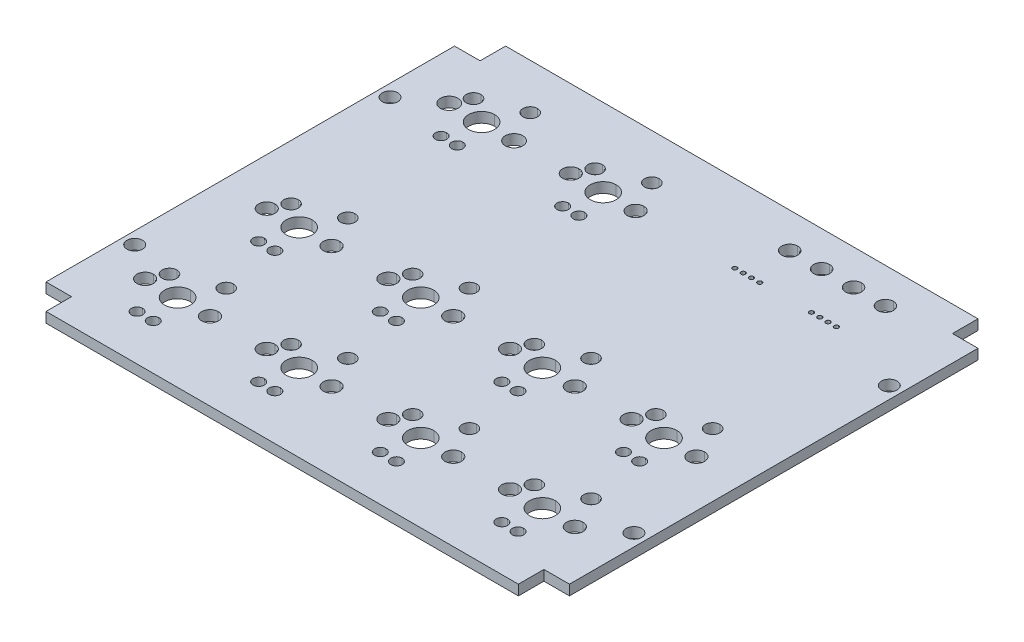
SolidWorks part; units mm, degrees
material "Copper"
ref_plane "Front" through (0, 0, 0) normal (0, 0, 1) x (1, 0, 0)
ref_plane "Top" through (0, 0, 0) normal (0, 1, 0) x (1, 0, 0)
ref_plane "Right" through (0, 0, 0) normal (1, 0, 0) x (0, 0, -1)
sketch "Sketch1" plane through (0, 0, 0) normal (0, 1, 0) x (1, 0, 0)
  line L0 (-41, 32) -> (-37, 32)
  line L1 (-37, 36) -> (37, 36)
  line L2 (-41, 32) -> (-41, -32)
  line L3 (-37, -36) -> (37, -36)
  line L4 (41, 32) -> (41, -32)
  line L5 (37, 36) -> (37, 32)
  line L6 (37, 32) -> (41, 32)
  line L7 (-37, 32) -> (-37, 36)
  line L8 (37, -36) -> (37, -32)
  line L9 (37, -32) -> (41, -32)
  line L10 (-37, -36) -> (-37, -32)
  line L11 (-37, -32) -> (-41, -32)
  line L12 (0, 36) -> (0, -36) construction
  dimension "D1" = 72
  dimension "D2" = 82
  dimension "D3" = 4
extrude "Boss-Extrude1" add sketch "Sketch1" along normal blind 1.6
sketch "Sketch2" plane through (0, 1.6, 0) normal (0, 1, 0) x (1, 0, 0)
  line L0 (-37, -36) -> (37, -36) construction
  line L1 (-41, 32) -> (-41, -32) construction
  line B0 (-41, -32) -> (-37, -32) construction
  line B1 (-37, -32) -> (-37, -36) construction
  line B2 (-37, -36) -> (36.9998, -36) construction
  line B3 (36.9998, -36) -> (36.9998, -32) construction
  line B4 (36.9998, -32) -> (40.9998, -32) construction
  line B5 (40.9998, -32) -> (40.9998, 31.9998) construction
  line B6 (40.9998, 31.9998) -> (36.9998, 31.9998) construction
  line B7 (36.9998, 31.9998) -> (36.9998, 35.9998) construction
  line B8 (36.9998, 35.9998) -> (-37, 35.9998) construction
  line B9 (-37, 35.9998) -> (-37, 31.9998) construction
  line B10 (-37, 31.9998) -> (-41, 31.9998) construction
  line B11 (-41, 31.9998) -> (-41, -32) construction
  spline B12 degree 3 poles (-28.5761, 21.7818) (-29.6983, 21.7818) (-30.6081, 22.6916) (-30.6081, 24.936) (-29.6983, 25.8458) (-28.5761, 25.8458) knots 2 2 2 2 3 3 4 4 4 4
  spline B13 degree 3 poles (-28.5761, 25.8458) (-27.4539, 25.8458) (-26.5441, 24.936) (-26.5441, 22.6916) (-27.4539, 21.7818) (-28.5761, 21.7818) knots 0 0 0 0 1 1 2 2 2 2
  spline B14 degree 3 poles (-9.5261, 21.7818) (-10.6484, 21.7818) (-11.5581, 22.6916) (-11.5581, 24.936) (-10.6484, 25.8458) (-9.5261, 25.8458) knots 2 2 2 2 3 3 4 4 4 4
  spline B15 degree 3 poles (-9.5261, 25.8458) (-8.4039, 25.8458) (-7.4942, 24.936) (-7.4942, 22.6916) (-8.4039, 21.7818) (-9.5261, 21.7818) knots 0 0 0 0 1 1 2 2 2 2
  spline B16 degree 3 poles (-28.5761, -6.7942) (-29.6983, -6.7942) (-30.6081, -5.8844) (-30.6081, -3.6399) (-29.6983, -2.7302) (-28.5761, -2.7302) knots 2 2 2 2 3 3 4 4 4 4
  spline B17 degree 3 poles (-28.5761, -2.7302) (-27.4539, -2.7302) (-26.5441, -3.6399) (-26.5441, -5.8844) (-27.4539, -6.7942) (-28.5761, -6.7942) knots 0 0 0 0 1 1 2 2 2 2
  spline B18 degree 3 poles (-9.5261, -6.7942) (-10.6484, -6.7942) (-11.5581, -5.8844) (-11.5581, -3.6399) (-10.6484, -2.7302) (-9.5261, -2.7302) knots 2 2 2 2 3 3 4 4 4 4
  spline B19 degree 3 poles (-9.5261, -2.7302) (-8.4039, -2.7302) (-7.4942, -3.6399) (-7.4942, -5.8844) (-8.4039, -6.7942) (-9.5261, -6.7942) knots 0 0 0 0 1 1 2 2 2 2
  spline B20 degree 3 poles (9.5238, -6.7942) (8.4015, -6.7942) (7.4918, -5.8844) (7.4918, -3.6399) (8.4015, -2.7302) (9.5238, -2.7302) knots 2 2 2 2 3 3 4 4 4 4
  spline B21 degree 3 poles (9.5238, -2.7302) (10.6461, -2.7302) (11.5558, -3.6399) (11.5558, -5.8844) (10.6461, -6.7942) (9.5238, -6.7942) knots 0 0 0 0 1 1 2 2 2 2
  spline B22 degree 3 poles (28.5738, -6.7942) (27.4515, -6.7942) (26.5418, -5.8844) (26.5418, -3.6399) (27.4515, -2.7302) (28.5738, -2.7302) knots 2 2 2 2 3 3 4 4 4 4
  spline B23 degree 3 poles (28.5738, -2.7302) (29.6961, -2.7302) (30.6058, -3.6399) (30.6058, -5.8844) (29.6961, -6.7942) (28.5738, -6.7942) knots 0 0 0 0 1 1 2 2 2 2
  spline B24 degree 3 poles (-28.5761, -25.8441) (-29.6983, -25.8441) (-30.6081, -24.9343) (-30.6081, -22.6899) (-29.6983, -21.7801) (-28.5761, -21.7801) knots 2 2 2 2 3 3 4 4 4 4
  spline B25 degree 3 poles (-28.5761, -21.7801) (-27.4539, -21.7801) (-26.5441, -22.6899) (-26.5441, -24.9343) (-27.4539, -25.8441) (-28.5761, -25.8441) knots 0 0 0 0 1 1 2 2 2 2
  spline B26 degree 3 poles (-9.5261, -25.8441) (-10.6484, -25.8441) (-11.5581, -24.9343) (-11.5581, -22.6899) (-10.6484, -21.7801) (-9.5261, -21.7801) knots 2 2 2 2 3 3 4 4 4 4
  spline B27 degree 3 poles (-9.5261, -21.7801) (-8.4039, -21.7801) (-7.4942, -22.6899) (-7.4942, -24.9343) (-8.4039, -25.8441) (-9.5261, -25.8441) knots 0 0 0 0 1 1 2 2 2 2
  spline B28 degree 3 poles (9.5238, -25.8441) (8.4015, -25.8441) (7.4918, -24.9343) (7.4918, -22.6899) (8.4015, -21.7801) (9.5238, -21.7801) knots 2 2 2 2 3 3 4 4 4 4
  spline B29 degree 3 poles (9.5238, -21.7801) (10.6461, -21.7801) (11.5558, -22.6899) (11.5558, -24.9343) (10.6461, -25.8441) (9.5238, -25.8441) knots 0 0 0 0 1 1 2 2 2 2
  spline B30 degree 3 poles (28.5738, -25.8441) (27.4515, -25.8441) (26.5418, -24.9343) (26.5418, -22.6899) (27.4515, -21.7801) (28.5738, -21.7801) knots 2 2 2 2 3 3 4 4 4 4
  spline B31 degree 3 poles (28.5738, -21.7801) (29.6961, -21.7801) (30.6058, -22.6899) (30.6058, -24.9343) (29.6961, -25.8441) (28.5738, -25.8441) knots 0 0 0 0 1 1 2 2 2 2
  spline B32 degree 3 poles (12.9998, 29.2499) (12.3095, 29.2499) (11.7498, 29.8095) (11.7498, 31.1902) (12.3095, 31.7498) (12.9998, 31.7498) knots 2 2 2 2 3 3 4 4 4 4
  spline B33 degree 3 poles (12.9998, 31.7498) (13.6901, 31.7498) (14.2498, 31.1902) (14.2498, 29.8095) (13.6901, 29.2499) (12.9998, 29.2499) knots 0 0 0 0 1 1 2 2 2 2
  spline B34 degree 3 poles (23, 29.2499) (22.3097, 29.2499) (21.75, 29.8095) (21.75, 31.1902) (22.3097, 31.7498) (23, 31.7498) knots 2 2 2 2 3 3 4 4 4 4
  spline B35 degree 3 poles (23, 31.7498) (23.6904, 31.7498) (24.2501, 31.1902) (24.2501, 29.8095) (23.6904, 29.2499) (23, 29.2499) knots 0 0 0 0 1 1 2 2 2 2
  spline B36 degree 3 poles (27.9999, 29.2499) (27.3096, 29.2499) (26.7499, 29.8095) (26.7499, 31.1902) (27.3096, 31.7498) (27.9999, 31.7498) knots 2 2 2 2 3 3 4 4 4 4
  spline B37 degree 3 poles (27.9999, 31.7498) (28.6902, 31.7498) (29.2499, 31.1902) (29.2499, 29.8095) (28.6902, 29.2499) (27.9999, 29.2499) knots 0 0 0 0 1 1 2 2 2 2
  spline B38 degree 3 poles (17.9998, 29.2499) (17.3095, 29.2499) (16.7498, 29.8095) (16.7498, 31.1902) (17.3095, 31.7498) (17.9998, 31.7498) knots 2 2 2 2 3 3 4 4 4 4
  spline B39 degree 3 poles (17.9998, 31.7498) (18.6901, 31.7498) (19.2498, 31.1902) (19.2498, 29.8095) (18.6901, 29.2499) (17.9998, 29.2499) knots 0 0 0 0 1 1 2 2 2 2
  spline B40 degree 3 poles (-32.3861, 25.2108) (-33.0174, 25.2108) (-33.5291, 25.7225) (-33.5291, 26.9851) (-33.0174, 27.4968) (-32.3861, 27.4968) knots 2 2 2 2 3 3 4 4 4 4
  spline B41 degree 3 poles (-32.3861, 27.4968) (-31.7548, 27.4968) (-31.2431, 26.9851) (-31.2431, 25.7225) (-31.7548, 25.2108) (-32.3861, 25.2108) knots 0 0 0 0 1 1 2 2 2 2
  spline B42 degree 3 poles (-26.0361, 27.7508) (-26.6674, 27.7508) (-27.1791, 28.2625) (-27.1791, 29.5251) (-26.6674, 30.0368) (-26.0361, 30.0368) knots 2 2 2 2 3 3 4 4 4 4
  spline B43 degree 3 poles (-26.0361, 30.0368) (-25.4048, 30.0368) (-24.8931, 29.5251) (-24.8931, 28.2625) (-25.4048, 27.7508) (-26.0361, 27.7508) knots 0 0 0 0 1 1 2 2 2 2
  spline B44 degree 3 poles (-33.6561, 22.5281) (-34.3662, 22.5281) (-34.9418, 23.1037) (-34.9418, 24.5239) (-34.3662, 25.0996) (-33.6561, 25.0996) knots 2 2 2 2 3 3 4 4 4 4
  spline B45 degree 3 poles (-33.6561, 25.0996) (-32.946, 25.0996) (-32.3703, 24.5239) (-32.3703, 23.1037) (-32.946, 22.5281) (-33.6561, 22.5281) knots 0 0 0 0 1 1 2 2 2 2
  spline B46 degree 3 poles (-23.4961, 22.5281) (-24.2062, 22.5281) (-24.7819, 23.1037) (-24.7819, 24.5239) (-24.2062, 25.0996) (-23.4961, 25.0996) knots 2 2 2 2 3 3 4 4 4 4
  spline B47 degree 3 poles (-23.4961, 25.0996) (-22.786, 25.0996) (-22.2104, 24.5239) (-22.2104, 23.1037) (-22.786, 22.5281) (-23.4961, 22.5281) knots 0 0 0 0 1 1 2 2 2 2
  spline B48 degree 3 poles (-29.8461, 17.8448) (-30.3371, 17.8448) (-30.7351, 18.2428) (-30.7351, 19.2248) (-30.3371, 19.6228) (-29.8461, 19.6228) knots 2 2 2 2 3 3 4 4 4 4
  spline B49 degree 3 poles (-29.8461, 19.6228) (-29.3551, 19.6228) (-28.9571, 19.2248) (-28.9571, 18.2428) (-29.3551, 17.8448) (-29.8461, 17.8448) knots 0 0 0 0 1 1 2 2 2 2
  spline B50 degree 3 poles (-27.3061, 17.8448) (-27.7971, 17.8448) (-28.1951, 18.2428) (-28.1951, 19.2248) (-27.7971, 19.6228) (-27.3061, 19.6228) knots 2 2 2 2 3 3 4 4 4 4
  spline B51 degree 3 poles (-27.3061, 19.6228) (-26.8151, 19.6228) (-26.4171, 19.2248) (-26.4171, 18.2428) (-26.8151, 17.8448) (-27.3061, 17.8448) knots 0 0 0 0 1 1 2 2 2 2
  spline B52 degree 3 poles (-13.3361, 25.2108) (-13.9674, 25.2108) (-14.4791, 25.7225) (-14.4791, 26.9851) (-13.9674, 27.4968) (-13.3361, 27.4968) knots 2 2 2 2 3 3 4 4 4 4
  spline B53 degree 3 poles (-13.3361, 27.4968) (-12.7049, 27.4968) (-12.1931, 26.9851) (-12.1931, 25.7225) (-12.7049, 25.2108) (-13.3361, 25.2108) knots 0 0 0 0 1 1 2 2 2 2
  spline B54 degree 3 poles (-6.9862, 27.7508) (-7.6174, 27.7508) (-8.1292, 28.2625) (-8.1292, 29.5251) (-7.6174, 30.0368) (-6.9862, 30.0368) knots 2 2 2 2 3 3 4 4 4 4
  spline B55 degree 3 poles (-6.9862, 30.0368) (-6.3549, 30.0368) (-5.8432, 29.5251) (-5.8432, 28.2625) (-6.3549, 27.7508) (-6.9862, 27.7508) knots 0 0 0 0 1 1 2 2 2 2
  spline B56 degree 3 poles (-14.6061, 22.5281) (-15.3163, 22.5281) (-15.8919, 23.1037) (-15.8919, 24.5239) (-15.3163, 25.0996) (-14.6061, 25.0996) knots 2 2 2 2 3 3 4 4 4 4
  spline B57 degree 3 poles (-14.6061, 25.0996) (-13.896, 25.0996) (-13.3204, 24.5239) (-13.3204, 23.1037) (-13.896, 22.5281) (-14.6061, 22.5281) knots 0 0 0 0 1 1 2 2 2 2
  spline B58 degree 3 poles (-4.4462, 22.5281) (-5.1563, 22.5281) (-5.7319, 23.1037) (-5.7319, 24.5239) (-5.1563, 25.0996) (-4.4462, 25.0996) knots 2 2 2 2 3 3 4 4 4 4
  spline B59 degree 3 poles (-4.4462, 25.0996) (-3.736, 25.0996) (-3.1604, 24.5239) (-3.1604, 23.1037) (-3.736, 22.5281) (-4.4462, 22.5281) knots 0 0 0 0 1 1 2 2 2 2
  spline B60 degree 3 poles (-10.7961, 17.8448) (-11.2872, 17.8448) (-11.6851, 18.2428) (-11.6851, 19.2248) (-11.2872, 19.6228) (-10.7961, 19.6228) knots 2 2 2 2 3 3 4 4 4 4
  spline B61 degree 3 poles (-10.7961, 19.6228) (-10.3051, 19.6228) (-9.9071, 19.2248) (-9.9071, 18.2428) (-10.3051, 17.8448) (-10.7961, 17.8448) knots 0 0 0 0 1 1 2 2 2 2
  spline B62 degree 3 poles (-8.2562, 17.8448) (-8.7472, 17.8448) (-9.1451, 18.2428) (-9.1451, 19.2248) (-8.7472, 19.6228) (-8.2562, 19.6228) knots 2 2 2 2 3 3 4 4 4 4
  spline B63 degree 3 poles (-8.2562, 19.6228) (-7.7651, 19.6228) (-7.3672, 19.2248) (-7.3672, 18.2428) (-7.7651, 17.8448) (-8.2562, 17.8448) knots 0 0 0 0 1 1 2 2 2 2
  spline B64 degree 3 poles (-32.3861, -3.3652) (-33.0174, -3.3652) (-33.5291, -2.8534) (-33.5291, -1.5909) (-33.0174, -1.0792) (-32.3861, -1.0792) knots 2 2 2 2 3 3 4 4 4 4
  spline B65 degree 3 poles (-32.3861, -1.0792) (-31.7548, -1.0792) (-31.2431, -1.5909) (-31.2431, -2.8534) (-31.7548, -3.3652) (-32.3861, -3.3652) knots 0 0 0 0 1 1 2 2 2 2
  spline B66 degree 3 poles (-26.0361, -0.8252) (-26.6674, -0.8252) (-27.1791, -0.3135) (-27.1791, 0.9491) (-26.6674, 1.4608) (-26.0361, 1.4608) knots 2 2 2 2 3 3 4 4 4 4
  spline B67 degree 3 poles (-26.0361, 1.4608) (-25.4048, 1.4608) (-24.8931, 0.9491) (-24.8931, -0.3135) (-25.4048, -0.8252) (-26.0361, -0.8252) knots 0 0 0 0 1 1 2 2 2 2
  spline B68 degree 3 poles (-33.6561, -6.0479) (-34.3662, -6.0479) (-34.9418, -5.4723) (-34.9418, -4.0521) (-34.3662, -3.4764) (-33.6561, -3.4764) knots 2 2 2 2 3 3 4 4 4 4
  spline B69 degree 3 poles (-33.6561, -3.4764) (-32.946, -3.4764) (-32.3703, -4.0521) (-32.3703, -5.4723) (-32.946, -6.0479) (-33.6561, -6.0479) knots 0 0 0 0 1 1 2 2 2 2
  spline B70 degree 3 poles (-23.4961, -6.0479) (-24.2062, -6.0479) (-24.7819, -5.4723) (-24.7819, -4.0521) (-24.2062, -3.4764) (-23.4961, -3.4764) knots 2 2 2 2 3 3 4 4 4 4
  spline B71 degree 3 poles (-23.4961, -3.4764) (-22.786, -3.4764) (-22.2104, -4.0521) (-22.2104, -5.4723) (-22.786, -6.0479) (-23.4961, -6.0479) knots 0 0 0 0 1 1 2 2 2 2
  spline B72 degree 3 poles (-29.8461, -10.7312) (-30.3371, -10.7312) (-30.7351, -10.3332) (-30.7351, -9.3511) (-30.3371, -8.9532) (-29.8461, -8.9532) knots 2 2 2 2 3 3 4 4 4 4
  spline B73 degree 3 poles (-29.8461, -8.9532) (-29.3551, -8.9532) (-28.9571, -9.3511) (-28.9571, -10.3332) (-29.3551, -10.7312) (-29.8461, -10.7312) knots 0 0 0 0 1 1 2 2 2 2
  spline B74 degree 3 poles (-27.3061, -10.7312) (-27.7971, -10.7312) (-28.1951, -10.3332) (-28.1951, -9.3511) (-27.7971, -8.9532) (-27.3061, -8.9532) knots 2 2 2 2 3 3 4 4 4 4
  spline B75 degree 3 poles (-27.3061, -8.9532) (-26.8151, -8.9532) (-26.4171, -9.3511) (-26.4171, -10.3332) (-26.8151, -10.7312) (-27.3061, -10.7312) knots 0 0 0 0 1 1 2 2 2 2
  spline B76 degree 3 poles (-13.3361, -3.3652) (-13.9674, -3.3652) (-14.4791, -2.8534) (-14.4791, -1.5909) (-13.9674, -1.0792) (-13.3361, -1.0792) knots 2 2 2 2 3 3 4 4 4 4
  spline B77 degree 3 poles (-13.3361, -1.0792) (-12.7049, -1.0792) (-12.1931, -1.5909) (-12.1931, -2.8534) (-12.7049, -3.3652) (-13.3361, -3.3652) knots 0 0 0 0 1 1 2 2 2 2
  spline B78 degree 3 poles (-6.9862, -0.8252) (-7.6174, -0.8252) (-8.1292, -0.3135) (-8.1292, 0.9491) (-7.6174, 1.4608) (-6.9862, 1.4608) knots 2 2 2 2 3 3 4 4 4 4
  spline B79 degree 3 poles (-6.9862, 1.4608) (-6.3549, 1.4608) (-5.8432, 0.9491) (-5.8432, -0.3135) (-6.3549, -0.8252) (-6.9862, -0.8252) knots 0 0 0 0 1 1 2 2 2 2
  spline B80 degree 3 poles (-14.6061, -6.0479) (-15.3163, -6.0479) (-15.8919, -5.4723) (-15.8919, -4.0521) (-15.3163, -3.4764) (-14.6061, -3.4764) knots 2 2 2 2 3 3 4 4 4 4
  spline B81 degree 3 poles (-14.6061, -3.4764) (-13.896, -3.4764) (-13.3204, -4.0521) (-13.3204, -5.4723) (-13.896, -6.0479) (-14.6061, -6.0479) knots 0 0 0 0 1 1 2 2 2 2
  spline B82 degree 3 poles (-4.4462, -6.0479) (-5.1563, -6.0479) (-5.7319, -5.4723) (-5.7319, -4.0521) (-5.1563, -3.4764) (-4.4462, -3.4764) knots 2 2 2 2 3 3 4 4 4 4
  spline B83 degree 3 poles (-4.4462, -3.4764) (-3.736, -3.4764) (-3.1604, -4.0521) (-3.1604, -5.4723) (-3.736, -6.0479) (-4.4462, -6.0479) knots 0 0 0 0 1 1 2 2 2 2
  spline B84 degree 3 poles (-10.7961, -10.7312) (-11.2872, -10.7312) (-11.6851, -10.3332) (-11.6851, -9.3511) (-11.2872, -8.9532) (-10.7961, -8.9532) knots 2 2 2 2 3 3 4 4 4 4
  spline B85 degree 3 poles (-10.7961, -8.9532) (-10.3051, -8.9532) (-9.9071, -9.3511) (-9.9071, -10.3332) (-10.3051, -10.7312) (-10.7961, -10.7312) knots 0 0 0 0 1 1 2 2 2 2
  spline B86 degree 3 poles (-8.2562, -10.7312) (-8.7472, -10.7312) (-9.1451, -10.3332) (-9.1451, -9.3511) (-8.7472, -8.9532) (-8.2562, -8.9532) knots 2 2 2 2 3 3 4 4 4 4
  spline B87 degree 3 poles (-8.2562, -8.9532) (-7.7651, -8.9532) (-7.3672, -9.3511) (-7.3672, -10.3332) (-7.7651, -10.7312) (-8.2562, -10.7312) knots 0 0 0 0 1 1 2 2 2 2
  spline B88 degree 3 poles (5.7138, -3.3652) (5.0825, -3.3652) (4.5708, -2.8534) (4.5708, -1.5909) (5.0825, -1.0792) (5.7138, -1.0792) knots 2 2 2 2 3 3 4 4 4 4
  spline B89 degree 3 poles (5.7138, -1.0792) (6.3451, -1.0792) (6.8568, -1.5909) (6.8568, -2.8534) (6.3451, -3.3652) (5.7138, -3.3652) knots 0 0 0 0 1 1 2 2 2 2
  spline B90 degree 3 poles (12.0638, -0.8252) (11.4325, -0.8252) (10.9208, -0.3135) (10.9208, 0.9491) (11.4325, 1.4608) (12.0638, 1.4608) knots 2 2 2 2 3 3 4 4 4 4
  spline B91 degree 3 poles (12.0638, 1.4608) (12.6951, 1.4608) (13.2068, 0.9491) (13.2068, -0.3135) (12.6951, -0.8252) (12.0638, -0.8252) knots 0 0 0 0 1 1 2 2 2 2
  spline B92 degree 3 poles (4.4438, -6.0479) (3.7337, -6.0479) (3.1581, -5.4723) (3.1581, -4.0521) (3.7337, -3.4764) (4.4438, -3.4764) knots 2 2 2 2 3 3 4 4 4 4
  spline B93 degree 3 poles (4.4438, -3.4764) (5.154, -3.4764) (5.7296, -4.0521) (5.7296, -5.4723) (5.154, -6.0479) (4.4438, -6.0479) knots 0 0 0 0 1 1 2 2 2 2
  spline B94 degree 3 poles (14.6038, -6.0479) (13.8936, -6.0479) (13.318, -5.4723) (13.318, -4.0521) (13.8936, -3.4764) (14.6038, -3.4764) knots 2 2 2 2 3 3 4 4 4 4
  spline B95 degree 3 poles (14.6038, -3.4764) (15.314, -3.4764) (15.8895, -4.0521) (15.8895, -5.4723) (15.314, -6.0479) (14.6038, -6.0479) knots 0 0 0 0 1 1 2 2 2 2
  spline B96 degree 3 poles (8.2538, -10.7312) (7.7628, -10.7312) (7.3648, -10.3332) (7.3648, -9.3511) (7.7628, -8.9532) (8.2538, -8.9532) knots 2 2 2 2 3 3 4 4 4 4
  spline B97 degree 3 poles (8.2538, -8.9532) (8.7448, -8.9532) (9.1428, -9.3511) (9.1428, -10.3332) (8.7448, -10.7312) (8.2538, -10.7312) knots 0 0 0 0 1 1 2 2 2 2
  spline B98 degree 3 poles (10.7938, -10.7312) (10.3028, -10.7312) (9.9048, -10.3332) (9.9048, -9.3511) (10.3028, -8.9532) (10.7938, -8.9532) knots 2 2 2 2 3 3 4 4 4 4
  spline B99 degree 3 poles (10.7938, -8.9532) (11.2848, -8.9532) (11.6828, -9.3511) (11.6828, -10.3332) (11.2848, -10.7312) (10.7938, -10.7312) knots 0 0 0 0 1 1 2 2 2 2
  spline B100 degree 3 poles (24.7638, -3.3652) (24.1325, -3.3652) (23.6208, -2.8534) (23.6208, -1.5909) (24.1325, -1.0792) (24.7638, -1.0792) knots 2 2 2 2 3 3 4 4 4 4
  spline B101 degree 3 poles (24.7638, -1.0792) (25.3951, -1.0792) (25.9068, -1.5909) (25.9068, -2.8534) (25.3951, -3.3652) (24.7638, -3.3652) knots 0 0 0 0 1 1 2 2 2 2
  spline B102 degree 3 poles (31.1138, -0.8252) (30.4825, -0.8252) (29.9708, -0.3135) (29.9708, 0.9491) (30.4825, 1.4608) (31.1138, 1.4608) knots 2 2 2 2 3 3 4 4 4 4
  spline B103 degree 3 poles (31.1138, 1.4608) (31.745, 1.4608) (32.2568, 0.9491) (32.2568, -0.3135) (31.745, -0.8252) (31.1138, -0.8252) knots 0 0 0 0 1 1 2 2 2 2
  spline B104 degree 3 poles (23.4938, -6.0479) (22.7836, -6.0479) (22.208, -5.4723) (22.208, -4.0521) (22.7836, -3.4764) (23.4938, -3.4764) knots 2 2 2 2 3 3 4 4 4 4
  spline B105 degree 3 poles (23.4938, -3.4764) (24.2039, -3.4764) (24.7795, -4.0521) (24.7795, -5.4723) (24.2039, -6.0479) (23.4938, -6.0479) knots 0 0 0 0 1 1 2 2 2 2
  spline B106 degree 3 poles (33.6538, -6.0479) (32.9436, -6.0479) (32.368, -5.4723) (32.368, -4.0521) (32.9436, -3.4764) (33.6538, -3.4764) knots 2 2 2 2 3 3 4 4 4 4
  spline B107 degree 3 poles (33.6538, -3.4764) (34.3639, -3.4764) (34.9395, -4.0521) (34.9395, -5.4723) (34.3639, -6.0479) (33.6538, -6.0479) knots 0 0 0 0 1 1 2 2 2 2
  spline B108 degree 3 poles (27.3038, -10.7312) (26.8128, -10.7312) (26.4148, -10.3332) (26.4148, -9.3511) (26.8128, -8.9532) (27.3038, -8.9532) knots 2 2 2 2 3 3 4 4 4 4
  spline B109 degree 3 poles (27.3038, -8.9532) (27.7948, -8.9532) (28.1928, -9.3511) (28.1928, -10.3332) (27.7948, -10.7312) (27.3038, -10.7312) knots 0 0 0 0 1 1 2 2 2 2
  spline B110 degree 3 poles (29.8438, -10.7312) (29.3528, -10.7312) (28.9548, -10.3332) (28.9548, -9.3511) (29.3528, -8.9532) (29.8438, -8.9532) knots 2 2 2 2 3 3 4 4 4 4
  spline B111 degree 3 poles (29.8438, -8.9532) (30.3348, -8.9532) (30.7328, -9.3511) (30.7328, -10.3332) (30.3348, -10.7312) (29.8438, -10.7312) knots 0 0 0 0 1 1 2 2 2 2
  spline B112 degree 3 poles (-32.3861, -22.4151) (-33.0174, -22.4151) (-33.5291, -21.9034) (-33.5291, -20.6408) (-33.0174, -20.1291) (-32.3861, -20.1291) knots 2 2 2 2 3 3 4 4 4 4
  spline B113 degree 3 poles (-32.3861, -20.1291) (-31.7548, -20.1291) (-31.2431, -20.6408) (-31.2431, -21.9034) (-31.7548, -22.4151) (-32.3861, -22.4151) knots 0 0 0 0 1 1 2 2 2 2
  spline B114 degree 3 poles (-26.0361, -19.8751) (-26.6674, -19.8751) (-27.1791, -19.3634) (-27.1791, -18.1009) (-26.6674, -17.5891) (-26.0361, -17.5891) knots 2 2 2 2 3 3 4 4 4 4
  spline B115 degree 3 poles (-26.0361, -17.5891) (-25.4048, -17.5891) (-24.8931, -18.1009) (-24.8931, -19.3634) (-25.4048, -19.8751) (-26.0361, -19.8751) knots 0 0 0 0 1 1 2 2 2 2
  spline B116 degree 3 poles (-33.6561, -25.0979) (-34.3662, -25.0979) (-34.9418, -24.5222) (-34.9418, -23.102) (-34.3662, -22.5264) (-33.6561, -22.5264) knots 2 2 2 2 3 3 4 4 4 4
  spline B117 degree 3 poles (-33.6561, -22.5264) (-32.946, -22.5264) (-32.3703, -23.102) (-32.3703, -24.5222) (-32.946, -25.0979) (-33.6561, -25.0979) knots 0 0 0 0 1 1 2 2 2 2
  spline B118 degree 3 poles (-23.4961, -25.0979) (-24.2062, -25.0979) (-24.7819, -24.5222) (-24.7819, -23.102) (-24.2062, -22.5264) (-23.4961, -22.5264) knots 2 2 2 2 3 3 4 4 4 4
  spline B119 degree 3 poles (-23.4961, -22.5264) (-22.786, -22.5264) (-22.2104, -23.102) (-22.2104, -24.5222) (-22.786, -25.0979) (-23.4961, -25.0979) knots 0 0 0 0 1 1 2 2 2 2
  spline B120 degree 3 poles (-29.8461, -29.7811) (-30.3371, -29.7811) (-30.7351, -29.3831) (-30.7351, -28.4011) (-30.3371, -28.0031) (-29.8461, -28.0031) knots 2 2 2 2 3 3 4 4 4 4
  spline B121 degree 3 poles (-29.8461, -28.0031) (-29.3551, -28.0031) (-28.9571, -28.4011) (-28.9571, -29.3831) (-29.3551, -29.7811) (-29.8461, -29.7811) knots 0 0 0 0 1 1 2 2 2 2
  spline B122 degree 3 poles (-27.3061, -29.7811) (-27.7971, -29.7811) (-28.1951, -29.3831) (-28.1951, -28.4011) (-27.7971, -28.0031) (-27.3061, -28.0031) knots 2 2 2 2 3 3 4 4 4 4
  spline B123 degree 3 poles (-27.3061, -28.0031) (-26.8151, -28.0031) (-26.4171, -28.4011) (-26.4171, -29.3831) (-26.8151, -29.7811) (-27.3061, -29.7811) knots 0 0 0 0 1 1 2 2 2 2
  spline B124 degree 3 poles (-13.3361, -22.4151) (-13.9674, -22.4151) (-14.4791, -21.9034) (-14.4791, -20.6408) (-13.9674, -20.1291) (-13.3361, -20.1291) knots 2 2 2 2 3 3 4 4 4 4
  spline B125 degree 3 poles (-13.3361, -20.1291) (-12.7049, -20.1291) (-12.1931, -20.6408) (-12.1931, -21.9034) (-12.7049, -22.4151) (-13.3361, -22.4151) knots 0 0 0 0 1 1 2 2 2 2
  spline B126 degree 3 poles (-6.9862, -19.8751) (-7.6174, -19.8751) (-8.1292, -19.3634) (-8.1292, -18.1009) (-7.6174, -17.5891) (-6.9862, -17.5891) knots 2 2 2 2 3 3 4 4 4 4
  spline B127 degree 3 poles (-6.9862, -17.5891) (-6.3549, -17.5891) (-5.8432, -18.1009) (-5.8432, -19.3634) (-6.3549, -19.8751) (-6.9862, -19.8751) knots 0 0 0 0 1 1 2 2 2 2
  spline B128 degree 3 poles (-14.6061, -25.0979) (-15.3163, -25.0979) (-15.8919, -24.5222) (-15.8919, -23.102) (-15.3163, -22.5264) (-14.6061, -22.5264) knots 2 2 2 2 3 3 4 4 4 4
  spline B129 degree 3 poles (-14.6061, -22.5264) (-13.896, -22.5264) (-13.3204, -23.102) (-13.3204, -24.5222) (-13.896, -25.0979) (-14.6061, -25.0979) knots 0 0 0 0 1 1 2 2 2 2
  spline B130 degree 3 poles (-4.4462, -25.0979) (-5.1563, -25.0979) (-5.7319, -24.5222) (-5.7319, -23.102) (-5.1563, -22.5264) (-4.4462, -22.5264) knots 2 2 2 2 3 3 4 4 4 4
  spline B131 degree 3 poles (-4.4462, -22.5264) (-3.736, -22.5264) (-3.1604, -23.102) (-3.1604, -24.5222) (-3.736, -25.0979) (-4.4462, -25.0979) knots 0 0 0 0 1 1 2 2 2 2
  spline B132 degree 3 poles (-10.7961, -29.7811) (-11.2872, -29.7811) (-11.6851, -29.3831) (-11.6851, -28.4011) (-11.2872, -28.0031) (-10.7961, -28.0031) knots 2 2 2 2 3 3 4 4 4 4
  spline B133 degree 3 poles (-10.7961, -28.0031) (-10.3051, -28.0031) (-9.9071, -28.4011) (-9.9071, -29.3831) (-10.3051, -29.7811) (-10.7961, -29.7811) knots 0 0 0 0 1 1 2 2 2 2
  spline B134 degree 3 poles (-8.2562, -29.7811) (-8.7472, -29.7811) (-9.1451, -29.3831) (-9.1451, -28.4011) (-8.7472, -28.0031) (-8.2562, -28.0031) knots 2 2 2 2 3 3 4 4 4 4
  spline B135 degree 3 poles (-8.2562, -28.0031) (-7.7651, -28.0031) (-7.3672, -28.4011) (-7.3672, -29.3831) (-7.7651, -29.7811) (-8.2562, -29.7811) knots 0 0 0 0 1 1 2 2 2 2
  spline B136 degree 3 poles (5.7138, -22.4151) (5.0825, -22.4151) (4.5708, -21.9034) (4.5708, -20.6408) (5.0825, -20.1291) (5.7138, -20.1291) knots 2 2 2 2 3 3 4 4 4 4
  spline B137 degree 3 poles (5.7138, -20.1291) (6.3451, -20.1291) (6.8568, -20.6408) (6.8568, -21.9034) (6.3451, -22.4151) (5.7138, -22.4151) knots 0 0 0 0 1 1 2 2 2 2
  spline B138 degree 3 poles (12.0638, -19.8751) (11.4325, -19.8751) (10.9208, -19.3634) (10.9208, -18.1009) (11.4325, -17.5891) (12.0638, -17.5891) knots 2 2 2 2 3 3 4 4 4 4
  spline B139 degree 3 poles (12.0638, -17.5891) (12.6951, -17.5891) (13.2068, -18.1009) (13.2068, -19.3634) (12.6951, -19.8751) (12.0638, -19.8751) knots 0 0 0 0 1 1 2 2 2 2
  spline B140 degree 3 poles (4.4438, -25.0979) (3.7337, -25.0979) (3.1581, -24.5222) (3.1581, -23.102) (3.7337, -22.5264) (4.4438, -22.5264) knots 2 2 2 2 3 3 4 4 4 4
  spline B141 degree 3 poles (4.4438, -22.5264) (5.154, -22.5264) (5.7296, -23.102) (5.7296, -24.5222) (5.154, -25.0979) (4.4438, -25.0979) knots 0 0 0 0 1 1 2 2 2 2
  spline B142 degree 3 poles (14.6038, -25.0979) (13.8936, -25.0979) (13.318, -24.5222) (13.318, -23.102) (13.8936, -22.5264) (14.6038, -22.5264) knots 2 2 2 2 3 3 4 4 4 4
  spline B143 degree 3 poles (14.6038, -22.5264) (15.314, -22.5264) (15.8895, -23.102) (15.8895, -24.5222) (15.314, -25.0979) (14.6038, -25.0979) knots 0 0 0 0 1 1 2 2 2 2
  spline B144 degree 3 poles (8.2538, -29.7811) (7.7628, -29.7811) (7.3648, -29.3831) (7.3648, -28.4011) (7.7628, -28.0031) (8.2538, -28.0031) knots 2 2 2 2 3 3 4 4 4 4
  spline B145 degree 3 poles (8.2538, -28.0031) (8.7448, -28.0031) (9.1428, -28.4011) (9.1428, -29.3831) (8.7448, -29.7811) (8.2538, -29.7811) knots 0 0 0 0 1 1 2 2 2 2
  spline B146 degree 3 poles (10.7938, -29.7811) (10.3028, -29.7811) (9.9048, -29.3831) (9.9048, -28.4011) (10.3028, -28.0031) (10.7938, -28.0031) knots 2 2 2 2 3 3 4 4 4 4
  spline B147 degree 3 poles (10.7938, -28.0031) (11.2848, -28.0031) (11.6828, -28.4011) (11.6828, -29.3831) (11.2848, -29.7811) (10.7938, -29.7811) knots 0 0 0 0 1 1 2 2 2 2
  spline B148 degree 3 poles (24.7638, -22.4151) (24.1325, -22.4151) (23.6208, -21.9034) (23.6208, -20.6408) (24.1325, -20.1291) (24.7638, -20.1291) knots 2 2 2 2 3 3 4 4 4 4
  spline B149 degree 3 poles (24.7638, -20.1291) (25.3951, -20.1291) (25.9068, -20.6408) (25.9068, -21.9034) (25.3951, -22.4151) (24.7638, -22.4151) knots 0 0 0 0 1 1 2 2 2 2
  spline B150 degree 3 poles (31.1138, -19.8751) (30.4825, -19.8751) (29.9708, -19.3634) (29.9708, -18.1009) (30.4825, -17.5891) (31.1138, -17.5891) knots 2 2 2 2 3 3 4 4 4 4
  spline B151 degree 3 poles (31.1138, -17.5891) (31.745, -17.5891) (32.2568, -18.1009) (32.2568, -19.3634) (31.745, -19.8751) (31.1138, -19.8751) knots 0 0 0 0 1 1 2 2 2 2
  spline B152 degree 3 poles (23.4938, -25.0979) (22.7836, -25.0979) (22.208, -24.5222) (22.208, -23.102) (22.7836, -22.5264) (23.4938, -22.5264) knots 2 2 2 2 3 3 4 4 4 4
  spline B153 degree 3 poles (23.4938, -22.5264) (24.2039, -22.5264) (24.7795, -23.102) (24.7795, -24.5222) (24.2039, -25.0979) (23.4938, -25.0979) knots 0 0 0 0 1 1 2 2 2 2
  spline B154 degree 3 poles (33.6538, -25.0979) (32.9436, -25.0979) (32.368, -24.5222) (32.368, -23.102) (32.9436, -22.5264) (33.6538, -22.5264) knots 2 2 2 2 3 3 4 4 4 4
  spline B155 degree 3 poles (33.6538, -22.5264) (34.3639, -22.5264) (34.9395, -23.102) (34.9395, -24.5222) (34.3639, -25.0979) (33.6538, -25.0979) knots 0 0 0 0 1 1 2 2 2 2
  spline B156 degree 3 poles (27.3038, -29.7811) (26.8128, -29.7811) (26.4148, -29.3831) (26.4148, -28.4011) (26.8128, -28.0031) (27.3038, -28.0031) knots 2 2 2 2 3 3 4 4 4 4
  spline B157 degree 3 poles (27.3038, -28.0031) (27.7948, -28.0031) (28.1928, -28.4011) (28.1928, -29.3831) (27.7948, -29.7811) (27.3038, -29.7811) knots 0 0 0 0 1 1 2 2 2 2
  spline B158 degree 3 poles (29.8438, -29.7811) (29.3528, -29.7811) (28.9548, -29.3831) (28.9548, -28.4011) (29.3528, -28.0031) (29.8438, -28.0031) knots 2 2 2 2 3 3 4 4 4 4
  spline B159 degree 3 poles (29.8438, -28.0031) (30.3348, -28.0031) (30.7328, -28.4011) (30.7328, -29.3831) (30.3348, -29.7811) (29.8438, -29.7811) knots 0 0 0 0 1 1 2 2 2 2
  spline B160 degree 3 poles (23.0994, 23.4677) (22.906, 23.4677) (22.7494, 23.6244) (22.7494, 24.011) (22.906, 24.1677) (23.0994, 24.1677) knots 2 2 2 2 3 3 4 4 4 4
  spline B161 degree 3 poles (23.0994, 24.1677) (23.2927, 24.1677) (23.4494, 24.011) (23.4494, 23.6244) (23.2927, 23.4677) (23.0994, 23.4677) knots 0 0 0 0 1 1 2 2 2 2
  spline B162 degree 3 poles (24.3994, 23.4677) (24.206, 23.4677) (24.0494, 23.6244) (24.0494, 24.011) (24.206, 24.1677) (24.3994, 24.1677) knots 2 2 2 2 3 3 4 4 4 4
  spline B163 degree 3 poles (24.3994, 24.1677) (24.5927, 24.1677) (24.7494, 24.011) (24.7494, 23.6244) (24.5927, 23.4677) (24.3994, 23.4677) knots 0 0 0 0 1 1 2 2 2 2
  spline B164 degree 3 poles (25.6994, 23.4677) (25.5061, 23.4677) (25.3494, 23.6244) (25.3494, 24.011) (25.5061, 24.1677) (25.6994, 24.1677) knots 2 2 2 2 3 3 4 4 4 4
  spline B165 degree 3 poles (25.6994, 24.1677) (25.8928, 24.1677) (26.0494, 24.011) (26.0494, 23.6244) (25.8928, 23.4677) (25.6994, 23.4677) knots 0 0 0 0 1 1 2 2 2 2
  spline B166 degree 3 poles (26.9994, 23.4677) (26.8061, 23.4677) (26.6494, 23.6244) (26.6494, 24.011) (26.8061, 24.1677) (26.9994, 24.1677) knots 2 2 2 2 3 3 4 4 4 4
  spline B167 degree 3 poles (26.9994, 24.1677) (27.1928, 24.1677) (27.3494, 24.011) (27.3494, 23.6244) (27.1928, 23.4677) (26.9994, 23.4677) knots 0 0 0 0 1 1 2 2 2 2
  spline B168 degree 3 poles (11.0994, 23.4677) (10.906, 23.4677) (10.7494, 23.6244) (10.7494, 24.011) (10.906, 24.1677) (11.0994, 24.1677) knots 2 2 2 2 3 3 4 4 4 4
  spline B169 degree 3 poles (11.0994, 24.1677) (11.2928, 24.1677) (11.4494, 24.011) (11.4494, 23.6244) (11.2928, 23.4677) (11.0994, 23.4677) knots 0 0 0 0 1 1 2 2 2 2
  spline B170 degree 3 poles (12.3994, 23.4677) (12.2061, 23.4677) (12.0494, 23.6244) (12.0494, 24.011) (12.2061, 24.1677) (12.3994, 24.1677) knots 2 2 2 2 3 3 4 4 4 4
  spline B171 degree 3 poles (12.3994, 24.1677) (12.5928, 24.1677) (12.7494, 24.011) (12.7494, 23.6244) (12.5928, 23.4677) (12.3994, 23.4677) knots 0 0 0 0 1 1 2 2 2 2
  spline B172 degree 3 poles (13.6994, 23.4677) (13.5061, 23.4677) (13.3494, 23.6244) (13.3494, 24.011) (13.5061, 24.1677) (13.6994, 24.1677) knots 2 2 2 2 3 3 4 4 4 4
  spline B173 degree 3 poles (13.6994, 24.1677) (13.8928, 24.1677) (14.0494, 24.011) (14.0494, 23.6244) (13.8928, 23.4677) (13.6994, 23.4677) knots 0 0 0 0 1 1 2 2 2 2
  spline B174 degree 3 poles (14.9994, 23.4677) (14.8061, 23.4677) (14.6494, 23.6244) (14.6494, 24.011) (14.8061, 24.1677) (14.9994, 24.1677) knots 2 2 2 2 3 3 4 4 4 4
  spline B175 degree 3 poles (14.9994, 24.1677) (15.1928, 24.1677) (15.3494, 24.011) (15.3494, 23.6244) (15.1928, 23.4677) (14.9994, 23.4677) knots 0 0 0 0 1 1 2 2 2 2
sketch_block_instance "Block1-1"
sketch_block "Block1"
extrude "Cut-Extrude1" cut sketch "Sketch2" against normal through all
sketch "Sketch3" plane through (0, 1.6, 0) normal (0, 1, 0) x (1, 0, 0)
  line L0 (-33.6561, 22.5281) -> (-33.6561, 25.0996) construction
  line L1 (-23.4961, 22.5281) -> (-23.4961, 25.0996) construction
  circle A2 centre (-33.6561, 23.8138) radius 1.375
  circle A3 centre (-23.4961, 23.8138) radius 1.375
  dimension "D1" = 2.75
extrude "Cut-Extrude2" cut sketch "Sketch3" against normal through all
sketch "Sketch4" plane through (0, 0, 0) normal (0, -1, 0) x (1, 0, 0)
  line L0 (-41, -32) -> (-41, 32) construction
  line L1 (0, 0) -> (0, -8.4843) construction
  line L2 (-39.1041, 0) -> (0, 0) construction
  circle A6 centre (-39.1041, 20) radius 1.2192
  circle A7 centre (-39.1041, -20) radius 1.2192
  circle A8 centre (39.1041, -20) radius 1.2192
  circle A9 centre (39.1041, 20) radius 1.2192
  point P16 (-39.1041, 0)
  dimension "D3" = 2.4384
  dimension "D1" = 20
  dimension "D2" = 20
  dimension "D4" = 1.8959
extrude "Cut-Extrude3" cut sketch "Sketch4" against normal through all
